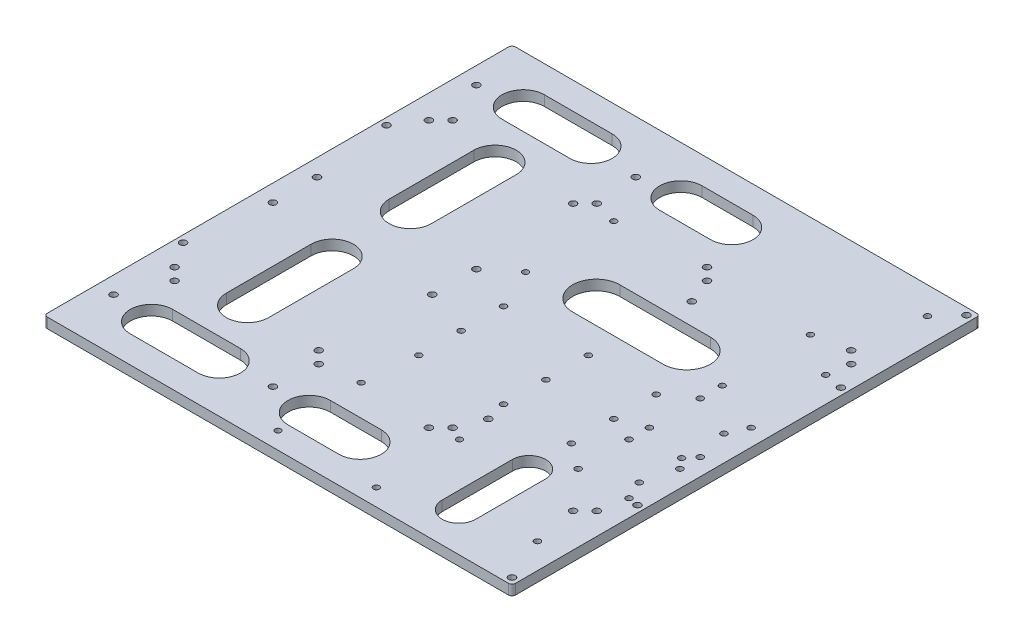
SolidWorks part; units mm, degrees
ref_plane "Спереди" through (0, 0, 0) normal (0, 0, 1) x (1, 0, 0)
ref_plane "Сверху" through (0, 0, 0) normal (0, 1, 0) x (1, 0, 0)
ref_plane "Справа" through (0, 0, 0) normal (1, 0, 0) x (0, 0, -1)
sketch "Эскиз1" plane through (0, 0, 0) normal (0, 1, 0) x (1, 0, 0)
  line L1 (-138, -138) -> (138, -138)
  line L2 (-138, -138) -> (-138, 138)
  line L3 (-138, 138) -> (138, 138)
  line L4 (138, -138) -> (138, 138)
  line L5 (0, 138) -> (0, -138) construction
  line L6 (-138, 0) -> (138, 0) construction
  point P0 (0, 0)
  dimension "D1" = 276
  dimension "D2" = 276
extrude "Бобышка-Вытянуть1" add sketch "Эскиз1" along normal blind 6
fillet "Скругление1" radius 2 4 edges at (138, 3, 138) (-138, 3, 138) (-138, 3, -138) (138, 3, -138)
sketch "Эскиз2" plane through (0, 6, 0) normal (0, 1, 0) x (1, 0, 0)
  line L0 (0, 147.7994) -> (0, 0) construction
  line L1 (0, 0) -> (-164.0684, 0) construction
  line L2 (-164.0684, 0) -> (215.1731, 0) construction
  circle A0 centre (-134, 60) radius 2
  circle A1 centre (134, 60) radius 2
  circle A2 centre (134, -60) radius 2
  circle A3 centre (-134, -60) radius 2
  circle A4 centre (46, 60) radius 2
  circle A5 centre (46, -60) radius 2
  circle A6 centre (134, 134) radius 2
  circle A7 centre (134, -134) radius 2
  dimension "D1" = 134
  dimension "D2" = 60
  dimension "D4" = 134
  dimension "D3" = 46
  dimension "D5" = 134
extrude "Вырез-Вытянуть1" cut sketch "Эскиз2" against normal blind 6
sketch "Эскиз3" plane through (0, 6, 0) normal (0, 1, 0) x (1, 0, 0)
  line L0 (0, 147.4317) -> (0, 0) construction
  line L1 (-193.8488, 0) -> (193.8488, 0) construction
  line L2 (138, -136) -> (138, 136) construction
  line L7 (43, 82) -> (43, -82) construction
  line L13 (43, 75) -> (43, -75) construction
  line L14 (-117, -82) -> (33, -82) construction
  line L16 (-117, 82) -> (33, 82) construction
  line L18 (-42, 82) -> (-42, -82) construction
  line L19 (-89.5005, 0) -> (60.4995, 0) construction
  line L20 (-124, -75) -> (40, -75) construction
  line L22 (-124, 75) -> (40, 75) construction
  line L24 (-42, 75) -> (-42, -75) construction
  line L25 (-96.5005, 0) -> (67.4995, 0) construction
  circle A0 centre (-32, 82) radius 2
  circle A1 centre (118, 82) radius 2
  circle A2 centre (125, 75) radius 2
  circle A3 centre (-39, 75) radius 2
  circle A4 centre (118, -82) radius 2
  circle A5 centre (125, -75) radius 2
  circle A6 centre (-32, -82) radius 2
  circle A7 centre (-39, -75) radius 2
  circle A8 centre (-124, 75) radius 2
  circle A10 centre (40, 75) radius 2
  circle A11 centre (33, 82) radius 2
  circle A12 centre (40, -75) radius 2
  circle A13 centre (33, -82) radius 2
  circle A14 centre (-117, -82) radius 2
  circle A15 centre (-124, -75) radius 2
  circle A16 centre (-117, 82) radius 2
  point P3 (43, 0)
  point P8 (43, 0)
  point P22 (-42, 0)
  point P24 (-42, 0)
  dimension "D3" = 95
  dimension "D1" = 150
  dimension "D2" = 164
  dimension "D4" = 150
  dimension "D5" = 164
  dimension "D6" = 180
extrude "150х164" cut sketch "Эскиз3" against normal blind 6
sketch "Эскиз4" plane through (0, 6, 0) normal (0, 1, 0) x (1, 0, 0)
  line L0 (-244.2183, 0) -> (0, 0) construction
  line L1 (0, 0) -> (0, 146.3288) construction
  line L2 (-177.488, 60) -> (64.2486, 60) construction
  line L3 (-138, 136) -> (-138, -136) construction
  line L4 (-128, 13) -> (-34, 13) construction
  line L5 (-128, 13) -> (-128, 107) construction
  line L6 (-128, 107) -> (-34, 107) construction
  line L7 (-34, 13) -> (-34, 107) construction
  line L8 (-81, 107) -> (-81, 13) construction
  line L9 (-128, 60) -> (-34, 60) construction
  circle A0 centre (-128, 107) radius 2
  circle A1 centre (-34, 107) radius 2
  circle A2 centre (-34, 13) radius 2
  circle A3 centre (-128, 13) radius 2
  circle A4 centre (-128, -13) radius 2
  circle A5 centre (-34, -13) radius 2
  circle A6 centre (-34, -107) radius 2
  circle A7 centre (-128, -107) radius 2
  point P6 (-81, 60)
  dimension "D1" = 94
  dimension "D2" = 94
  dimension "D3" = 60
  dimension "D4" = 10
extrude "94х94" cut sketch "Эскиз4" against normal blind 6
sketch "Эскиз7" plane through (0, 6, 0) normal (0, 1, 0) x (1, 0, 0)
  line L0 (-167.0096, 52) -> (194.2165, 52) construction
  line L2 (-18, 26) -> (98, 26) construction
  line L3 (-18, 26) -> (-18, 78) construction
  line L4 (-18, 78) -> (98, 78) construction
  line L5 (98, 26) -> (98, 78) construction
  line L6 (40, 78) -> (40, 26) construction
  line L7 (-18, 52) -> (98, 52) construction
  line L8 (136, 138) -> (-136, 138) construction
  circle A0 centre (-18, 78) radius 1.75
  circle A1 centre (-18, 26) radius 1.75
  circle A2 centre (98, 78) radius 1.75
  circle A3 centre (98, 26) radius 1.75
  point P2 (40, 52)
  dimension "D3" = 3.5
  dimension "D1" = 116
  dimension "D2" = 52
  dimension "D4" = 40
  dimension "D5" = 60
extrude "Jetson" cut sketch "Эскиз7" against normal blind 6
sketch "Эскиз8" plane through (0, 6, 0) normal (0, 1, 0) x (1, 0, 0)
  line L0 (-136, -138) -> (136, -138) construction
  line L1 (-10, -128) -> (48, -128) construction
  line L2 (-10, -128) -> (-10, -79) construction
  line L3 (-10, -79) -> (48, -79) construction
  line L4 (48, -128) -> (48, -79) construction
  line L5 (19, -79) -> (19, -128) construction
  line L6 (-10, -103.5) -> (48, -103.5) construction
  line L7 (138, -136) -> (138, 136) construction
  circle A0 centre (48, -79) radius 1.75
  circle A1 centre (-10, -79) radius 1.75
  circle A2 centre (-10, -128) radius 1.75
  circle A3 centre (48, -128) radius 1.75
  point P0 (19, -103.5)
  dimension "D5" = 3.5
  dimension "D1" = 58
  dimension "D2" = 49
  dimension "D3" = 10
  dimension "D4" = 90
extrude "Вырез-Вытянуть7" cut sketch "Эскиз8" against normal blind 6
sketch "Эскиз9" plane through (0, 6, 0) normal (0, 1, 0) x (1, 0, 0)
  line L0 (-18.2911, 15.2367) -> (-18.2911, -61.2367) construction
  line L1 (-18.2911, -61.2367) -> (91.6393, -61.2367) construction
  line L2 (91.6393, -61.2367) -> (91.6393, -138) construction
  line L3 (-136, -138) -> (136, -138) construction
  line L4 (91.6393, -138) -> (129.5083, -138) construction
  line L5 (129.5083, -138) -> (129.5083, 138) construction
  line L6 (136, 138) -> (-136, 138) construction
  line L7 (129.5083, 138) -> (112.5959, 138) construction
  line L8 (112.5959, 138) -> (112.5959, 17.8103) construction
  line L9 (112.5959, 17.8103) -> (-18.2911, 17.8103) construction
  line L10 (-18.2911, 17.8103) -> (-18.2911, 15.2367) construction
  line L11 (-18.2911, -23) -> (230.269, -23) construction
  line L12 (138, -136) -> (138, 136) construction
  line L13 (-7, 2) -> (-7, -48) construction
  line L14 (43, 2) -> (43, -48) construction
  line L15 (43, -48) -> (83, -48) construction
  line L16 (83, -48) -> (83, 2) construction
  line L17 (83, 2) -> (123, 2) construction
  line L18 (123, 2) -> (123, -48) construction
  line L19 (98, -17) -> (128, -17) construction
  line L26 (98, -17) -> (98, 13) construction
  line L27 (98, 13) -> (128, 13) construction
  line L28 (128, -17) -> (128, 13) construction
  line L29 (113, 13) -> (113, -17) construction
  line L30 (98, -2) -> (128, -2) construction
  circle A0 centre (-7, 2) radius 1.8
  circle A1 centre (43, 2) radius 1.8
  circle A2 centre (83, 2) radius 1.8
  circle A3 centre (123, 2) radius 1.8
  circle A4 centre (123, -48) radius 1.8
  circle A5 centre (83, -48) radius 1.8
  circle A6 centre (43, -48) radius 1.8
  circle A7 centre (-7, -48) radius 1.8
  circle A8 centre (43, -23) radius 1.8
  circle A9 centre (-7, -23) radius 1.8
  circle A10 centre (83, -23) radius 1.8
  circle A11 centre (123, -23) radius 1.8
  circle A12 centre (123, 62) radius 1.8
  circle A13 centre (123, 122) radius 1.8
  circle A15 centre (123, -108) radius 1.8
  circle A20 centre (98, 13) radius 1.8
  circle A21 centre (128, 13) radius 1.8
  circle A22 centre (98, -17) radius 1.8
  circle A23 centre (128, -17) radius 1.8
  circle A24 centre (98, -29) radius 1.8
  circle A25 centre (128, -29) radius 1.8
  circle A26 centre (128, -59) radius 1.8
  circle A27 centre (98, -59) radius 1.8
  point P61 (113, -2)
  dimension "D1" = 3.6
  dimension "D2" = 50
  dimension "D3" = 40
  dimension "D4" = 40
  dimension "D12" = 30
  dimension "D5" = 25
  dimension "D6" = 60
  dimension "D7" = 60
  dimension "D8" = 115
  dimension "D9" = 15
  dimension "D13" = 30
  dimension "D14" = 10
  dimension "D15" = 140
extrude "Вырез-Вытянуть8" cut sketch "Эскиз9" against normal blind 6
sketch "Эскиз6" plane through (0, 6, 0) normal (0, 1, 0) x (1, 0, 0)
  line L0 (-10, 109.6079) -> (20, 109.6079) construction
  line L1 (-10, 122.1079) -> (20, 122.1079)
  line L2 (-10, 97.1079) -> (20, 97.1079)
  line L3 (0, 56.0682) -> (0, 0) construction
  line L4 (0, 0) -> (164.436, 0) construction
  line L5 (-10, -109.6079) -> (20, -109.6079) construction
  line L6 (-10, -122.1079) -> (20, -122.1079)
  line L7 (-10, -97.1079) -> (20, -97.1079)
  line L8 (5, 131.99) -> (5, -109.6079) construction
  line L9 (-103, 109.6079) -> (-63, 109.6079) construction
  line L10 (-103, 122.1079) -> (-63, 122.1079)
  line L11 (-103, 97.1079) -> (-63, 97.1079)
  line L12 (-138, 136) -> (-138, -136) construction
  line L13 (-103, -109.6079) -> (-63, -109.6079) construction
  line L14 (-103, -122.1079) -> (-63, -122.1079)
  line L15 (-103, -97.1079) -> (-63, -97.1079)
  line L16 (-83, -73) -> (-83, -23) construction
  line L17 (-95.5, -73) -> (-95.5, -23)
  line L18 (-70.5, -73) -> (-70.5, -23)
  line L19 (-136, -138) -> (136, -138) construction
  line L20 (-83, 73) -> (-83, 23) construction
  line L21 (-95.5, 73) -> (-95.5, 23)
  line L22 (-70.5, 73) -> (-70.5, 23)
  line L23 (16.2821, 33.3891) -> (69.672, 33.3891) construction
  line L24 (16.2821, 47.2974) -> (69.672, 47.2974)
  line L25 (16.2821, 19.4808) -> (69.672, 19.4808)
  line L26 (83.6865, -73.6486) -> (83.6865, -114.9629) construction
  line L27 (93.5556, -73.6486) -> (93.5556, -114.9629)
  line L28 (73.8173, -73.6486) -> (73.8173, -114.9629)
  arc A0 (-10, 122.1079) -> (-10, 97.1079) centre (-10, 109.6079) ccw
  arc A1 (20, 97.1079) -> (20, 122.1079) centre (20, 109.6079) ccw
  arc A2 (-10, -122.1079) -> (-10, -97.1079) centre (-10, -109.6079) cw
  arc A3 (20, -97.1079) -> (20, -122.1079) centre (20, -109.6079) cw
  arc A4 (-103, 122.1079) -> (-103, 97.1079) centre (-103, 109.6079) ccw
  arc A5 (-63, 97.1079) -> (-63, 122.1079) centre (-63, 109.6079) ccw
  arc A6 (-103, -122.1079) -> (-103, -97.1079) centre (-103, -109.6079) cw
  arc A7 (-63, -97.1079) -> (-63, -122.1079) centre (-63, -109.6079) cw
  arc A8 (-95.5, -73) -> (-70.5, -73) centre (-83, -73) ccw
  arc A9 (-70.5, -23) -> (-95.5, -23) centre (-83, -23) ccw
  arc A10 (-95.5, 73) -> (-70.5, 73) centre (-83, 73) cw
  arc A11 (-70.5, 23) -> (-95.5, 23) centre (-83, 23) cw
  arc A12 (16.2821, 47.2974) -> (16.2821, 19.4808) centre (16.2821, 33.3891) ccw
  arc A13 (69.672, 19.4808) -> (69.672, 47.2974) centre (69.672, 33.3891) ccw
  arc A14 (93.5556, -73.6486) -> (73.8173, -73.6486) centre (83.6865, -73.6486) ccw
  arc A15 (73.8173, -114.9629) -> (93.5556, -114.9629) centre (83.6865, -114.9629) ccw
  point P2 (5, 109.6079)
  point P13 (5, -109.6079)
  point P22 (-83, 109.6079)
  point P31 (-83, -109.6079)
  point P38 (-83, -48)
  point P47 (-83, 48)
  point P54 (42.977, 33.3891)
  point P61 (83.6865, -94.3058)
  dimension "D1" = 30
  dimension "D2" = 25
  dimension "D3" = 5
  dimension "D4" = 40
  dimension "D5" = 25
  dimension "D6" = 55
  dimension "D7" = 25
  dimension "D8" = 50
  dimension "D9" = 90
extrude "Вырез-Вытянуть5" cut sketch "Эскиз6" against normal blind 6 contours L11 A5 L10 A4 | A11 L22 A10 L21 | L18 A9 L17 A8 | A7 L15 A6 L14 | L25 A13 L24 A12 | L28 A15 L27 A14 | A3 L7 A2 L6 | L2 A1 L1 A0
